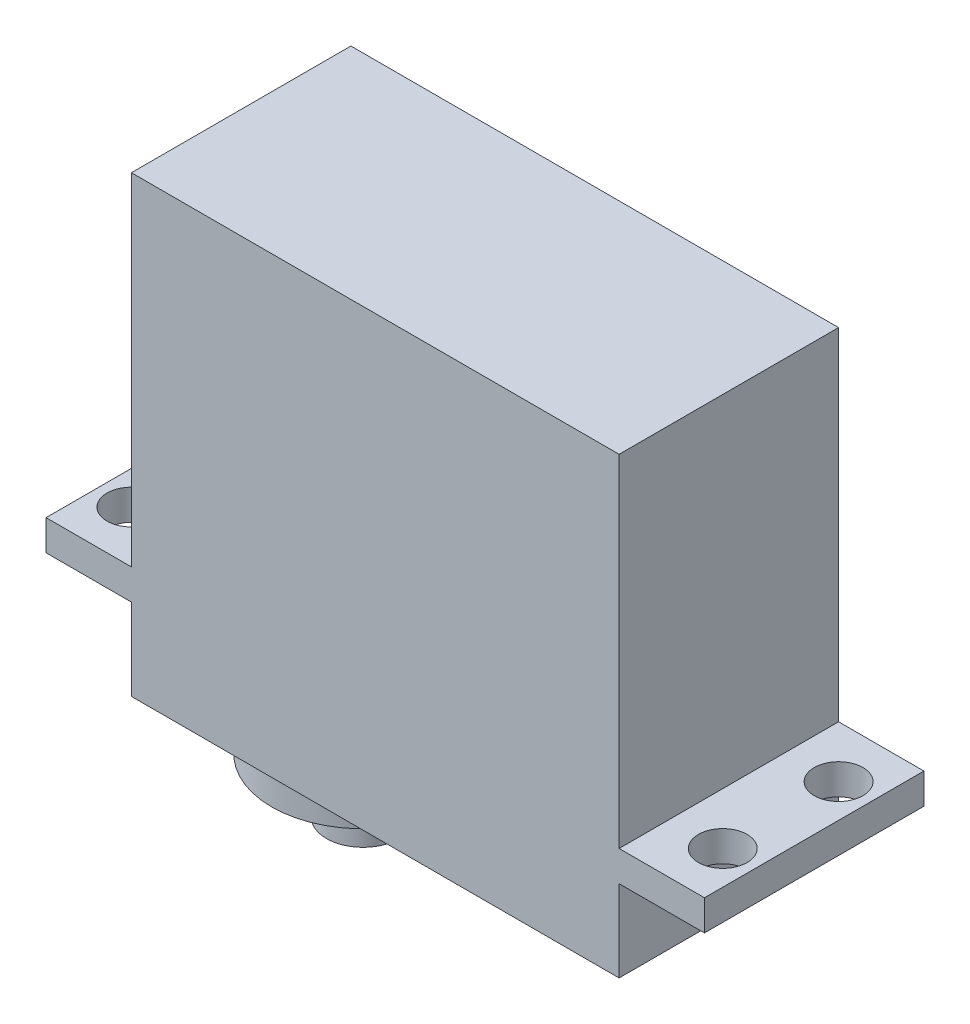
SolidWorks part; units mm, degrees
ref_plane "前视基准面" through (0, 0, 0) normal (0, 0, 1) x (1, 0, 0)
ref_plane "上视基准面" through (0, 0, 0) normal (0, 1, 0) x (1, 0, 0)
ref_plane "右视基准面" through (0, 0, 0) normal (1, 0, 0) x (0, 0, -1)
other "Configuration Table"
sketch "草图1" plane through (0, 0, 0) normal (0, 1, 0) x (1, 0, 0)
  line L1 (-27, -9) -> (27, -9)
  line L2 (-27, -9) -> (-27, 9)
  line L3 (-27, 9) -> (27, 9)
  line L4 (27, -9) -> (27, 9)
  line L5 (-27, -9) -> (27, 9) construction
  line L6 (-27, 9) -> (27, -9) construction
  point P0 (0, 0)
  dimension "D1" = 54
  dimension "D2" = 18
extrude "凸台-拉伸1" add sketch "草图1" along normal blind 2.5
sketch "草图2" plane through (0, 2.5, 0) normal (0, 1, 0) x (1, 0, 0)
  line L0 (-27, -9) -> (27, -9) construction
  line L1 (-20, 9) -> (20, 9)
  line L2 (-20, 9) -> (-20, -9)
  line L3 (-20, -9) -> (20, -9)
  line L4 (20, 9) -> (20, -9)
  line L5 (-20, 9) -> (20, -9) construction
  line L6 (-20, -9) -> (20, 9) construction
  point P0 (0, 0)
  dimension "D1" = 40
extrude "凸台-拉伸2" add sketch "草图2" along normal blind 28
sketch "草图3" plane through (0, 0, 0) normal (0, -1, 0) x (1, 0, 0)
  line L0 (-27, 9) -> (27, 9) construction
  line L1 (-20, -9) -> (20, -9)
  line L2 (-20, -9) -> (-20, 9)
  line L3 (-20, 9) -> (20, 9)
  line L4 (20, -9) -> (20, 9)
  line L5 (-20, -9) -> (20, 9) construction
  line L6 (-20, 9) -> (20, -9) construction
  point P0 (0, 0)
  dimension "D1" = 40
extrude "凸台-拉伸3" add sketch "草图3" along normal blind 6.7
sketch "草图4" plane through (0, -6.7, 0) normal (0, -1, 0) x (1, 0, 0)
  line L0 (-20, 9) -> (-20, -9) construction
  circle A0 centre (-10, 0) radius 7.5
  dimension "D2" = 15
  dimension "D1" = 10
extrude "凸台-拉伸4" add sketch "草图4" along normal blind 3.6
sketch "草图5" plane through (0, -10.3, 0) normal (0, -1, 0) x (1, 0, 0)
  circle A0 centre (-10, 0) radius 3
  dimension "D1" = 6
extrude "凸台-拉伸5" add sketch "草图5" along normal blind 4.5
sketch "草图6" plane through (0, 0, 0) normal (0, -1, 0) x (1, 0, 0)
  line L1 (-24.25, -4.75) -> (24.25, -4.75) construction
  line L2 (-24.25, -4.75) -> (-24.25, 4.75) construction
  line L3 (-24.25, 4.75) -> (24.25, 4.75) construction
  line L4 (24.25, -4.75) -> (24.25, 4.75) construction
  line L5 (-24.25, -4.75) -> (24.25, 4.75) construction
  line L6 (-24.25, 4.75) -> (24.25, -4.75) construction
  circle A0 centre (-24.25, 4.75) radius 2
  circle A1 centre (-24.25, -4.75) radius 2
  circle A2 centre (24.25, 4.75) radius 2
  circle A3 centre (24.25, -4.75) radius 2
  point P0 (0, 0)
  dimension "D3" = 4
  dimension "D4" = 4
  dimension "D5" = 4
  dimension "D6" = 4
  dimension "D1" = 48.5
  dimension "D2" = 9.5
extrude "切除-拉伸1" cut sketch "草图6" against normal blind 4.5
